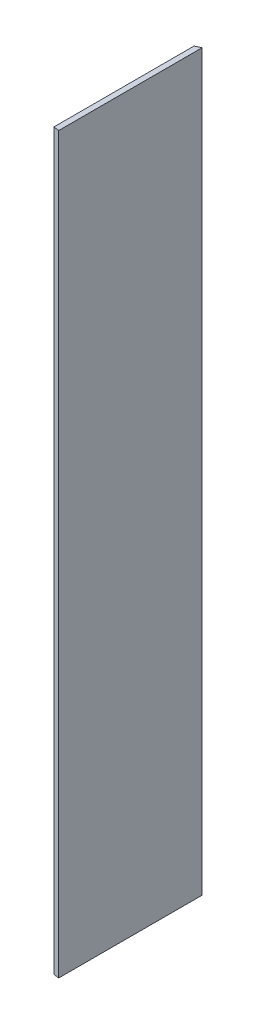
SolidWorks part; units mm, degrees
ref_plane "Спереди" through (0, 0, 0) normal (0, 0, 1) x (1, 0, 0)
ref_plane "Сверху" through (0, 0, 0) normal (0, 1, 0) x (1, 0, 0)
ref_plane "Справа" through (0, 0, 0) normal (1, 0, 0) x (0, 0, -1)
sketch "Эскиз1" plane through (0, 0, 0) normal (0, 1, 0) x (1, 0, 0)
  line L0 (1.0264, -5.5532) -> (1.0264, -107.3249)
  line L1 (1.0264, -107.3249) -> (5.0264, -107.8388)
  line L2 (5.0264, -107.8388) -> (5.0264, -3.7635)
  line L3 (5.0264, -3.7635) -> (1.0264, -5.5532)
  line L4 (0.2179, -107.1085) -> (4.8056, -108.3365) construction
  dimension "D1" = 4
extrude "Вытянуть1" add sketch "Эскиз1" along normal blind 533
